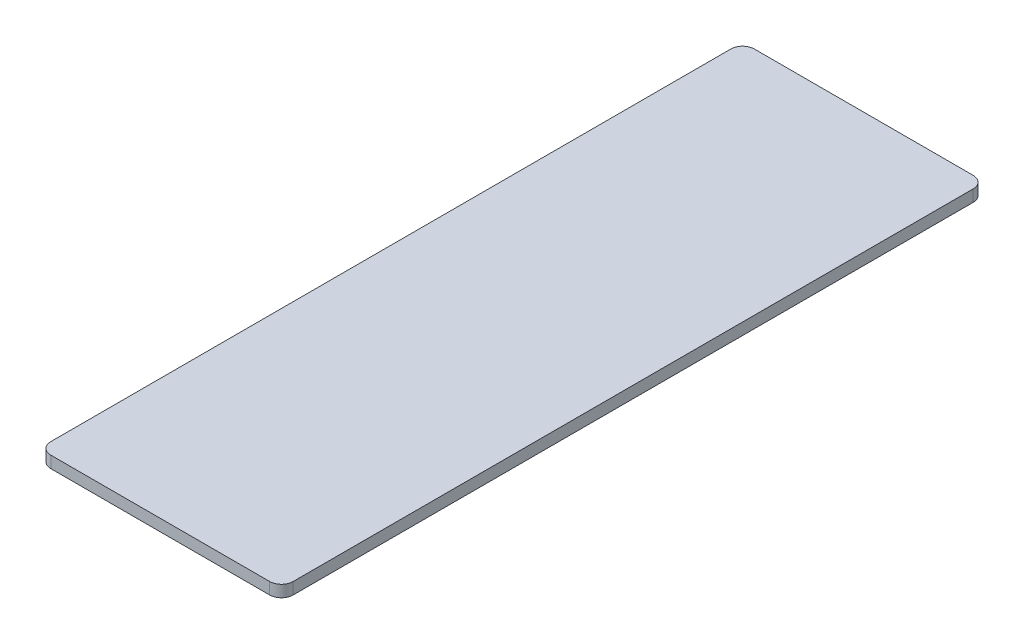
SolidWorks part; units mm, degrees
material "PET"
ref_plane "Front Plane" through (0, 0, 0) normal (0, 0, 1) x (1, 0, 0)
ref_plane "Top Plane" through (0, 0, 0) normal (0, 1, 0) x (1, 0, 0)
ref_plane "Right Plane" through (0, 0, 0) normal (1, 0, 0) x (0, 0, -1)
sketch "Sketch1" plane through (0, 0, 0) normal (0, 1, 0) x (1, 0, 0)
  line L1 (-28, 90) -> (28, 90)
  line L2 (-31, 87) -> (-31, -87)
  line L3 (-28, -90) -> (28, -90)
  line L4 (31, 87) -> (31, -87)
  line L5 (-31, 90) -> (31, -90) construction
  line L6 (-31, -90) -> (31, 90) construction
  arc A0 (28, -90) -> (31, -87) centre (28, -87) ccw
  arc A1 (-31, -87) -> (-28, -90) centre (-28, -87) ccw
  arc A2 (28, 90) -> (31, 87) centre (28, 87) cw
  arc A3 (-28, 90) -> (-31, 87) centre (-28, 87) ccw
  point P0 (0, 0)
  dimension "D3" = 3
  dimension "D1" = 62
  dimension "D2" = 180
extrude "Spine_Body" add sketch "Sketch1" along normal mid plane 3
sketch "Sketch2" plane through (0, 1.5, 0) normal (0, 1, 0) x (1, 0, 0)
  line L0 (0, 0) -> (9.8089, 0) construction
  circle A2 centre (-25, -102) radius 1.6
  circle A3 centre (25, -102) radius 1.6
  circle A4 centre (25, 102) radius 1.6
  circle A5 centre (-25, 102) radius 1.6
  dimension "D1" = 3.2
  dimension "D4" = 3.2
  dimension "D5" = 102
  dimension "D7" = 25
  dimension "D8" = 25
extrude "Tab_Holes" [suppressed] cut sketch "Sketch2" against normal through all
equation "\"Sp_L\" = 180mm"
equation "\"Sp_W\"= 62mm"
equation "\"Sp_T\"= 3mm"
equation "\"D2@Sketch1\"=\"Sp_L\""
equation "\"D1@Sketch1\"=\"Sp_W\""
equation "\"D1@Spine_Body\"=\"Sp_T\""
